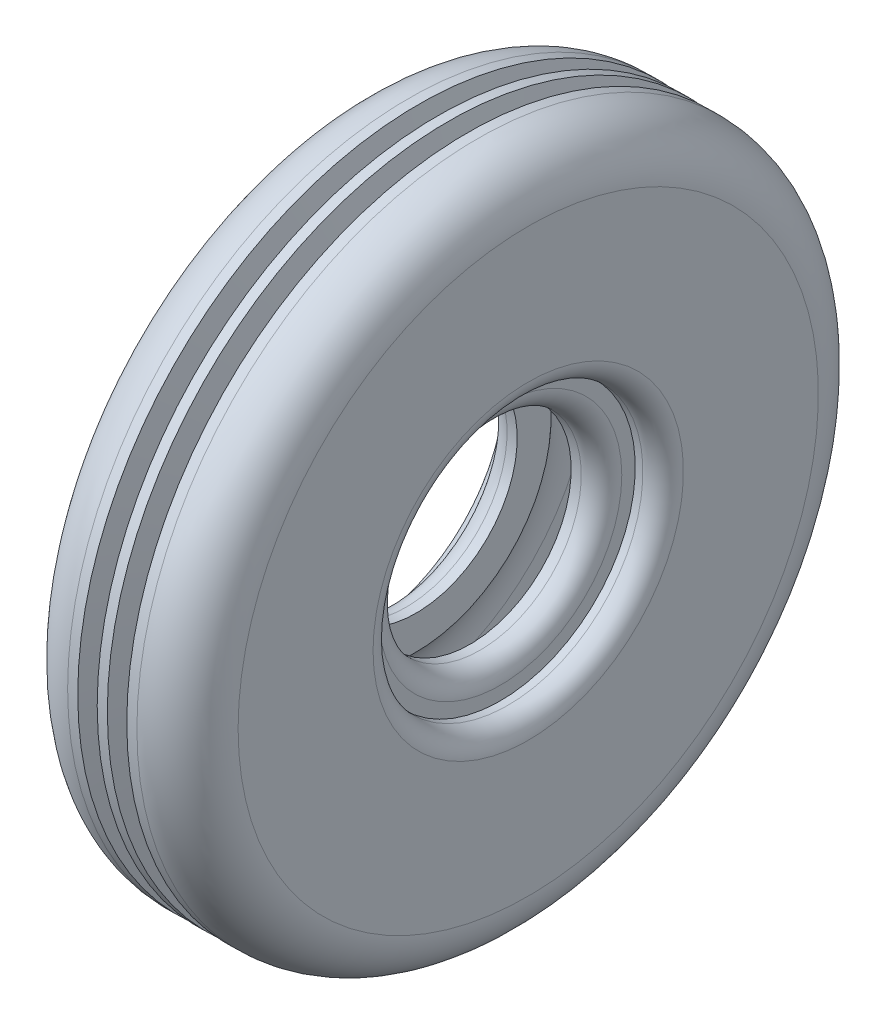
SolidWorks part; units mm, degrees
material "BUTYL"
ref_plane "Plan de face" through (0, 0, 0) normal (0, 0, 1) x (1, 0, 0)
ref_plane "Plan de dessus" through (0, 0, 0) normal (0, 1, 0) x (1, 0, 0)
ref_plane "Plan de droite" through (0, 0, 0) normal (1, 0, 0) x (0, 0, -1)
sketch "Esquisse1" plane through (0, 0, 0) normal (0, 0, 1) x (1, 0, 0)
  line L0 (0, 0) -> (0, 200) construction
  line L4 (241.8936, 300) -> (241.8936, 430)
  line L6 (-10.7616, 430) -> (-10.7616, 300)
  line L7 (75.566, 150) -> (75.566, 200)
  line L13 (155.566, 200) -> (155.566, 150)
  line L14 (155.566, 150) -> (170.566, 150)
  line L15 (30.566, 200) -> (30.566, 180)
  line L16 (60.566, 150) -> (75.566, 150)
  line L17 (200.566, 200) -> (200.566, 180)
  line L18 (64.2384, 430) -> (166.8936, 430)
  line L19 (34.2384, 400) -> (34.2384, 300)
  line L21 (196.8936, 400) -> (196.8936, 300)
  line L22 (0, 0) -> (173.2483, 0) construction
  line L23 (64.2384, 505) -> (79.2384, 505)
  line L24 (79.2384, 505) -> (88.6522, 466.1235)
  line L25 (88.6522, 466.1235) -> (98.6522, 466.1235)
  line L26 (98.6522, 466.1235) -> (108.066, 505)
  line L27 (108.066, 505) -> (123.066, 505)
  line L28 (123.066, 505) -> (132.4798, 466.1235)
  line L29 (132.4798, 466.1235) -> (142.4798, 466.1235)
  line L30 (142.4798, 466.1235) -> (151.8936, 505)
  line L31 (151.8936, 505) -> (166.8936, 505)
  line L34 (-10.7616, 230) -> (-10.7616, 300)
  line L39 (30.566, 200) -> (19.2384, 200)
  line L40 (200.566, 200) -> (211.8936, 200)
  line L41 (241.8936, 230) -> (241.8936, 300)
  arc A0 (166.8936, 505) -> (241.8936, 430) centre (166.8936, 430) cw
  arc A1 (-10.7616, 430) -> (64.2384, 505) centre (64.2384, 430) cw
  arc A4 (64.2384, 430) -> (34.2384, 400) centre (64.2384, 400) ccw
  arc A5 (166.8936, 430) -> (196.8936, 400) centre (166.8936, 400) cw
  arc A6 (34.2384, 300) -> (75.566, 200) centre (175.8867, 300) ccw
  arc A7 (196.8936, 300) -> (155.566, 200) centre (55.2453, 300) cw
  arc A9 (19.2384, 200) -> (-10.7616, 230) centre (19.2384, 230) cw
  arc A10 (211.8936, 200) -> (241.8936, 230) centre (211.8936, 230) ccw
  arc A11 (30.566, 180) -> (60.566, 150) centre (60.566, 180) ccw
  arc A12 (200.566, 180) -> (170.566, 150) centre (170.566, 180) cw
  point P41 (241.8936, 200)
  point P43 (241.8936, 200)
  point P46 (30.566, 150)
  point P49 (200.566, 150)
  dimension "D3" = 75
  dimension "D5" = 41.3276
  dimension "D11" = 30
  dimension "D12" = 30
  dimension "D22" = 30
  dimension "D23" = 30
  dimension "D24" = 30
  dimension "D25" = 30
  dimension "D4" = 150
  dimension "D6" = 50
  dimension "D7" = 45
  dimension "D8" = 45
  dimension "D9" = 50
  dimension "D10" = 200
  dimension "D13" = 100
  dimension "D14" = 100
  dimension "D15" = 15
  dimension "D16" = 10
  dimension "D17" = 40
  dimension "D18" = 40
  dimension "D19" = 40
  dimension "D20" = 40
  dimension "D21" = 170
revolve "Révolution1" add sketch "Esquisse1" angle 360 about L22
